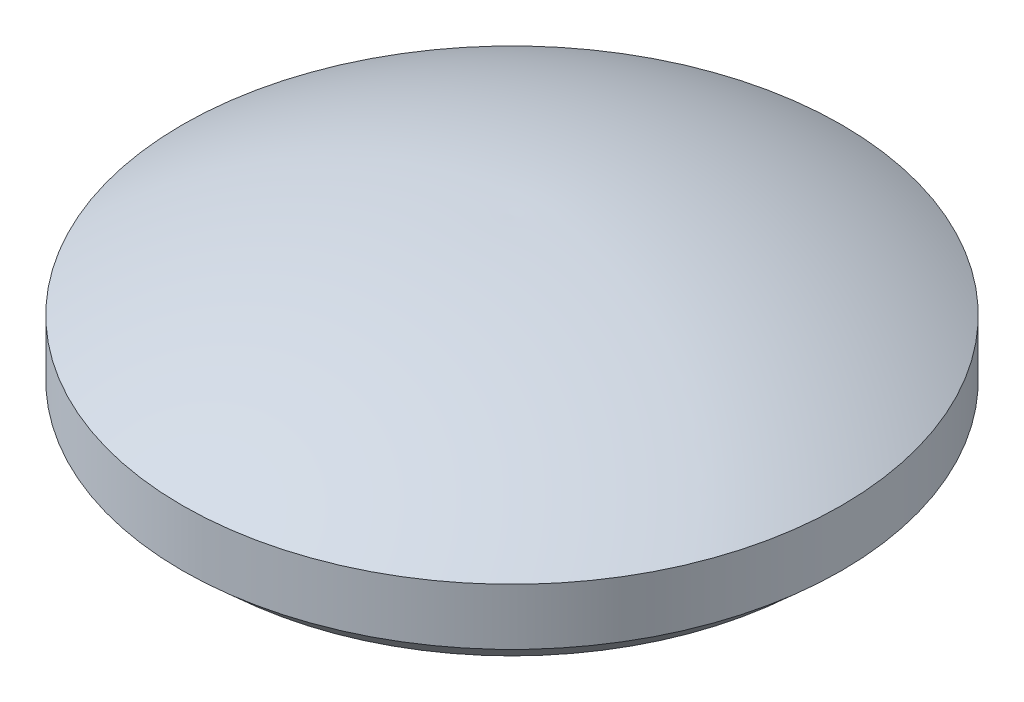
SolidWorks part; units mm, degrees
ref_plane "Front" through (0, 0, 0) normal (0, 0, 1) x (1, 0, 0)
ref_plane "Top" through (0, 0, 0) normal (0, 1, 0) x (1, 0, 0)
ref_plane "Right" through (0, 0, 0) normal (1, 0, 0) x (0, 0, -1)
sketch "Sketch1" plane through (0, 0, 0) normal (0, 0, 1) x (1, 0, 0)
  line L0 (0, 0) -> (0, 65)
  line L1 (0, 0) -> (22.5, 0)
  line L2 (22.5, 0) -> (51.3438, 26)
  line L3 (51.3438, 26) -> (69.3438, 26)
  line L4 (69.3438, 26) -> (76, 32)
  line L5 (76, 32) -> (76, 45)
  arc A0 (0, 65) -> (76, 45) centre (2.7437, -78.9739) cw
  dimension "D1" = 76
  dimension "D8" = 144
  dimension "D2" = 65
  dimension "D3" = 45
  dimension "D4" = 32
  dimension "D5" = 18
  dimension "D6" = 22.5
  dimension "D7" = 26
revolve "Revolve1" add sketch "Sketch1" angle 360 about L0
ref_point "Point1"
